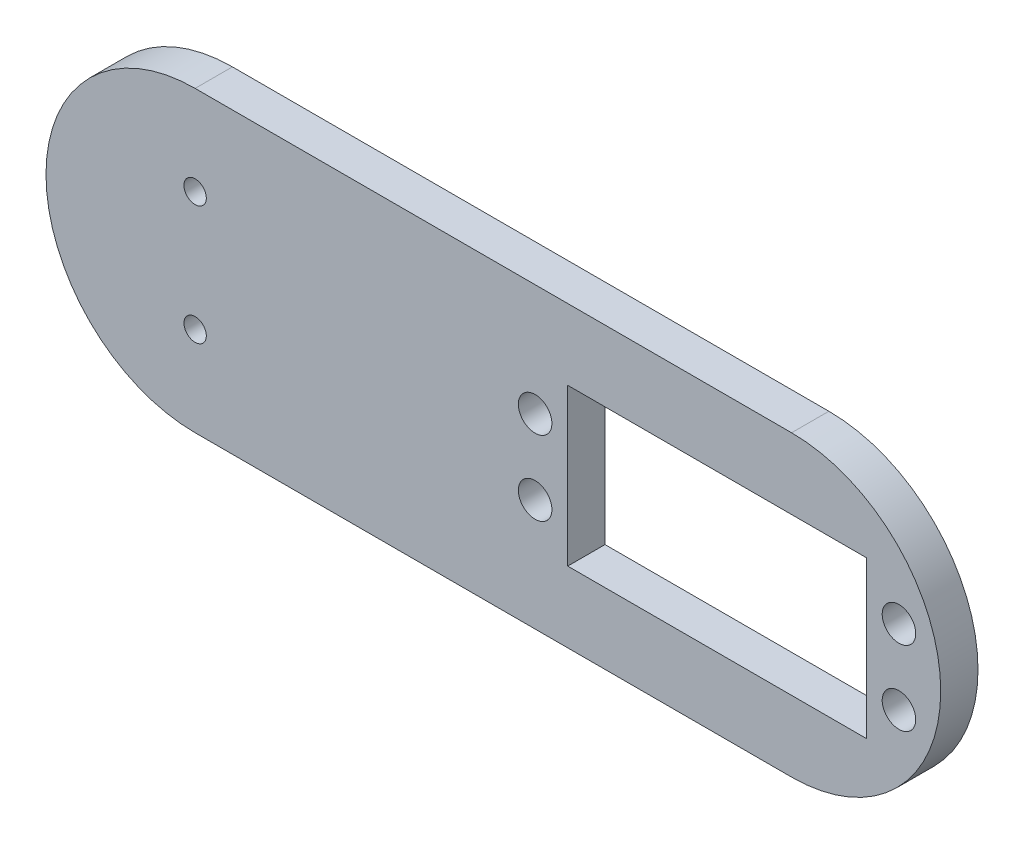
SolidWorks part; units mm, degrees
material "Acrylic (Medium-high impact)"
ref_plane "Front Plane" through (0, 0, 0) normal (0, 0, 1) x (1, 0, 0)
ref_plane "Top Plane" through (0, 0, 0) normal (0, 1, 0) x (1, 0, 0)
ref_plane "Right Plane" through (0, 0, 0) normal (1, 0, 0) x (0, 0, -1)
sketch "Sketch1" plane through (0, 0, 0) normal (0, 1, 0) x (1, 0, 0)
  line L0 (80, -20) -> (0, -20)
  line L2 (0, 20) -> (80, 20)
  line L3 (0, 0) -> (0, 6.474) construction
  line L4 (80, 0) -> (80, 8.2666) construction
  line L5 (80, 0) -> (185.7321, 0) construction
  arc A0 (0, 20) -> (0, -20) centre (0, 0) ccw
  arc A1 (80, -20) -> (80, 20) centre (80, 0) ccw
  circle A2 centre (60, -13.0415) radius 2.3527
  circle A3 centre (60, 13.0415) radius 2.3527
  dimension "D1" = 40
  dimension "D3" = 80
  dimension "D4" = 6.9585
  dimension "D5" = 20
  dimension "D2" = 2
extrude "Boss-Extrude1" add sketch "Sketch1" along normal blind 5 contours L2 A1 L0 A0
sketch "Sketch2" plane through (0, 5, 0) normal (0, 1, 0) x (1, 0, 0)
  circle A1 centre (0.002, 8) radius 1.5
  circle A5 centre (0.002, -8) radius 1.5
  circle A8 centre (8.002, 0) radius 1.5 [skipped]
  circle A9 centre (-7.998, 0) radius 1.5 [skipped]
  point P20 (0.002, 0)
  dimension "D1" = 8
  dimension "D2" = 3
  dimension "D4" = 16
  dimension "D3" = 4
extrude "Cut-Extrude1" cut sketch "Sketch2" against normal up to next
move or copy body "Body-Move/Copy1" bodies to move or copy 102 copy no rotation origin (0, 0, 0) rotation axis (1, 0, 0) rotation angle 90
sketch "Sketch19" plane through (0, 0, 5) normal (0, 0, 1) x (1, 0, 0)
  line L0 (80, 20) -> (80, -20) construction
  line L1 (100, 0) -> (170.0596, 0) construction
  line L3 (49.975, -10.5) -> (90.025, -10.5)
  line L4 (49.975, -10.5) -> (49.975, 10.5)
  line L5 (49.975, 10.5) -> (90.025, 10.5)
  line L6 (90.025, -10.5) -> (90.025, 10.5)
  line L7 (49.975, -10.5) -> (90.025, 10.5) construction
  line L8 (49.975, 10.5) -> (90.025, -10.5) construction
  arc A0 (80, -20) -> (80, 20) centre (80, 0) ccw construction
  circle A1 centre (94.4, -5) radius 2.25
  circle A2 centre (94.4, 5) radius 2.25
  circle A3 centre (45.6, 5) radius 2.25
  circle A4 centre (45.6, -5) radius 2.25
  point P0 (80, 0)
  point P21 (70, 0)
  dimension "D1" = 4.5
  dimension "D2" = 5
  dimension "D3" = 14.4
  dimension "D5" = 48.8
  dimension "D6" = 24.4
  dimension "D7" = 40.05
  dimension "D8" = 21
  dimension "D4" = 2
extrude "Cut-Extrude9" cut sketch "Sketch19" against normal through all
sketch "Sketch20" plane through (0, 0, 0) normal (0, 0, -1) x (-1, 0, 0)
  line L0 (0, 0) -> (-13.4581, 0) construction
move or copy body "Body-Move/Copy5" bodies to move or copy 124 copy no translate (-120, 0, 0)
move or copy body "Body-Move/Copy6" bodies to move or copy 129 copy no translate (0, 0, -5)
